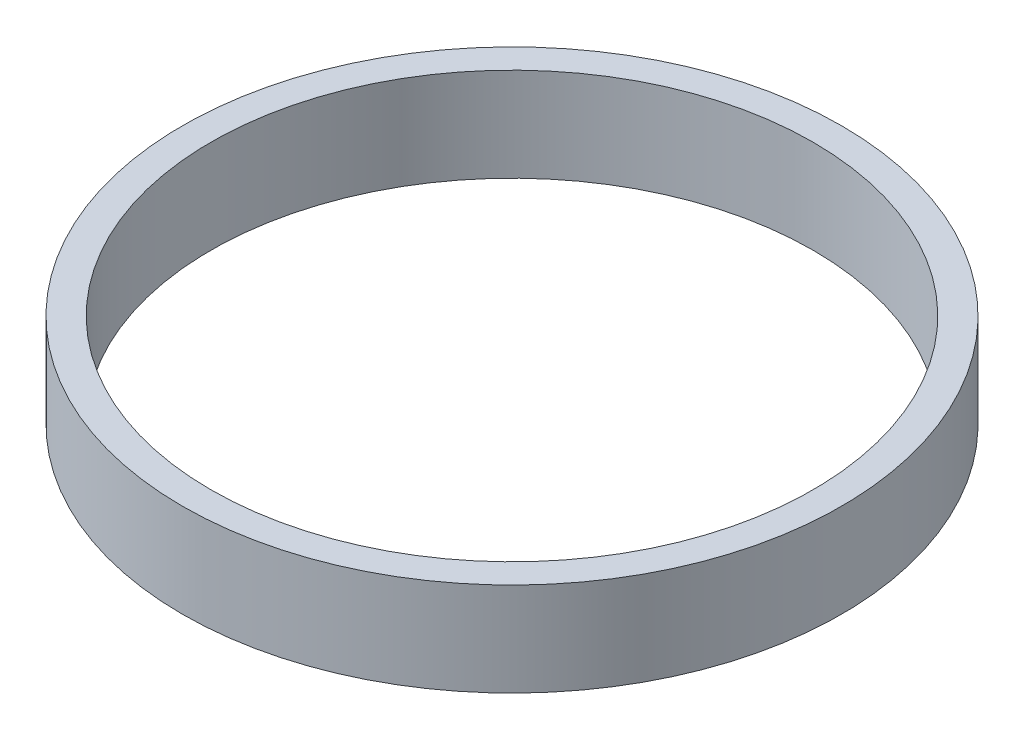
SolidWorks part; units mm, degrees
ref_plane "Front Plane" through (0, 0, 0) normal (0, 0, 1) x (1, 0, 0)
ref_plane "Top Plane" through (0, 0, 0) normal (0, 1, 0) x (1, 0, 0)
ref_plane "Right Plane" through (0, 0, 0) normal (1, 0, 0) x (0, 0, -1)
other "Configuration Table"
sketch "Sketch1" plane through (0, 0, 0) normal (0, 1, 0) x (1, 0, 0)
  circle A0 centre (0, 0) radius 40.5
extrude "YUVA_icecek_halka_1" add sketch "Sketch1" along normal blind 11.5 from offset 6.5 separate body
sketch "Sketch2" plane through (0, 0, 0) normal (0, 1, 0) x (1, 0, 0)
  circle A0 centre (0, 0) radius 37
extrude "YUVA_icecek_halka_2" cut sketch "Sketch2" along normal blind 13 from offset 6
